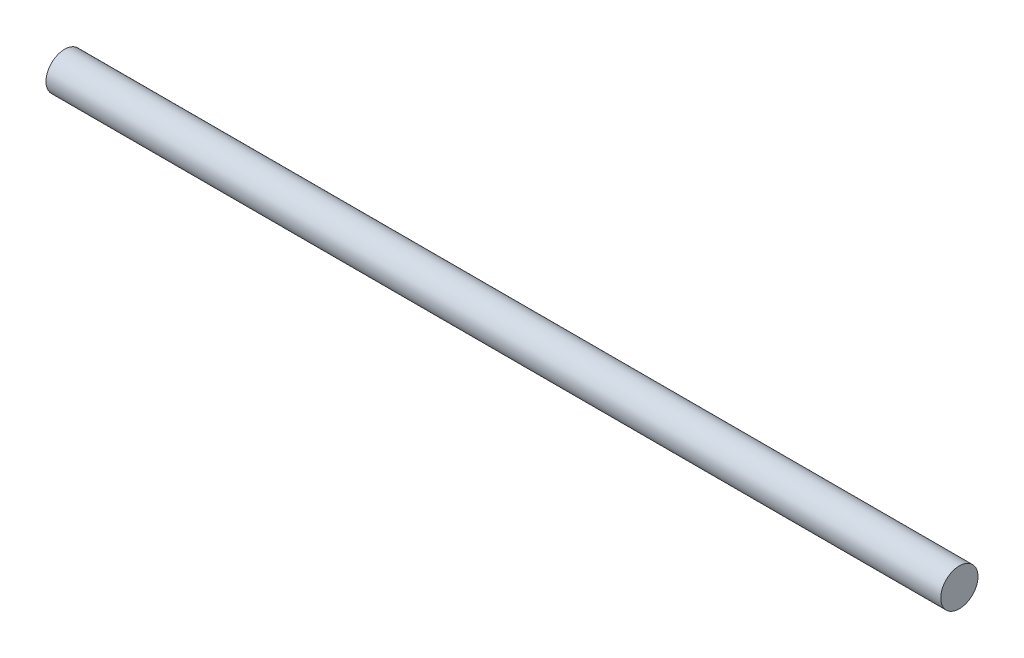
SolidWorks part; units mm, degrees
ref_plane "Front Plane" through (0, 0, 0) normal (0, 0, 1) x (1, 0, 0)
ref_plane "Top Plane" through (0, 0, 0) normal (0, 1, 0) x (1, 0, 0)
ref_plane "Right Plane" through (0, 0, 0) normal (1, 0, 0) x (0, 0, -1)
sketch "Sketch1" plane through (0, 0, 0) normal (1, 0, 0) x (0, 0, -1)
  circle A0 centre (0, 0) radius 1.25
extrude "Boss-Extrude1" add sketch "Sketch1" along normal blind 60
